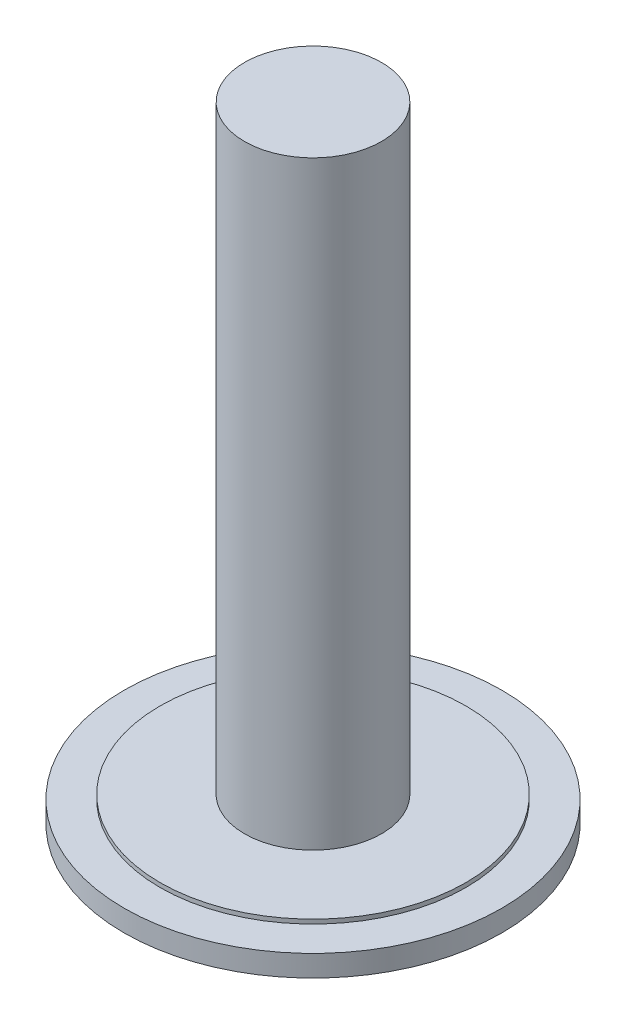
SolidWorks part; units mm, degrees
ref_plane "Front Plane" through (0, 0, 0) normal (0, 0, 1) x (1, 0, 0)
ref_plane "Top Plane" through (0, 0, 0) normal (0, 1, 0) x (1, 0, 0)
ref_plane "Right Plane" through (0, 0, 0) normal (1, 0, 0) x (0, 0, -1)
sketch "Sketch1" plane through (0, 0, 0) normal (0, 1, 0) x (1, 0, 0)
  circle A0 centre (0, 0) radius 11.025
  dimension "D1" = 22.05
extrude "Boss-Extrude1" add sketch "Sketch1" along normal blind 1.5
sketch "Sketch2" plane through (0, 1.5, 0) normal (0, 1, 0) x (1, 0, 0)
  circle A0 centre (0, 0) radius 11.025
  circle A1 centre (0, 0) radius 8.9305
extrude "Cut-Extrude1" cut sketch "Sketch2" against normal blind 0.25
sketch "Sketch3" plane through (0, 1.5, 0) normal (0, 1, 0) x (1, 0, 0)
  circle A0 centre (0, 0) radius 4
  dimension "D1" = 8
extrude "Boss-Extrude2" add sketch "Sketch3" along normal blind 35
